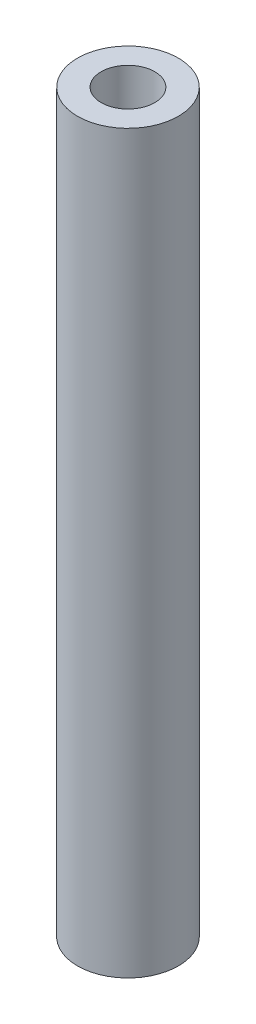
SolidWorks part; units mm, degrees
material "6061-T6 (SS)"
ref_plane "Front Plane" through (0, 0, 0) normal (0, 0, 1) x (1, 0, 0)
ref_plane "Top Plane" through (0, 0, 0) normal (0, 1, 0) x (1, 0, 0)
ref_plane "Right Plane" through (0, 0, 0) normal (1, 0, 0) x (0, 0, -1)
sketch "Sketch1" plane through (0, 0, 0) normal (0, 1, 0) x (1, 0, 0)
  circle A0 centre (0, 0) radius 9.398
  circle A1 centre (0, 0) radius 5
  dimension "D1" = 18.796
  dimension "D2" = 10
extrude "Boss-Extrude1" add sketch "Sketch1" along normal blind 137.16
